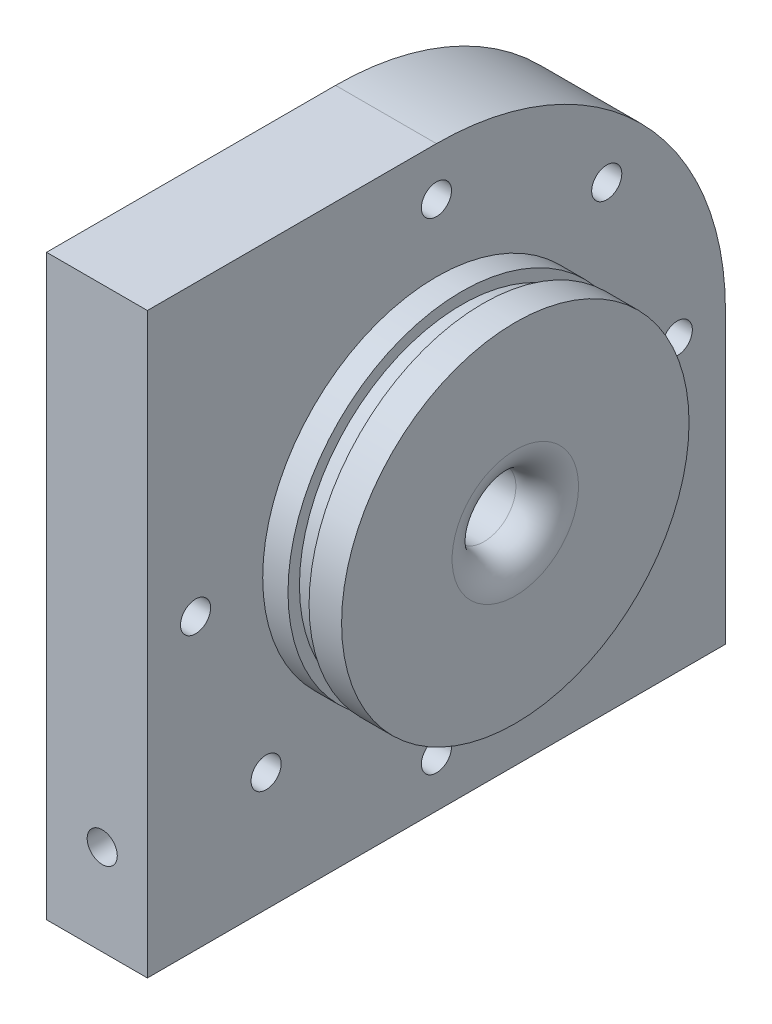
SolidWorks part; units mm, degrees
material "6061 Alloy"
ref_plane "Front Plane" through (0, 0, 0) normal (0, 0, 1) x (1, 0, 0)
ref_plane "Top Plane" through (0, 0, 0) normal (0, 1, 0) x (1, 0, 0)
ref_plane "Right Plane" through (0, 0, 0) normal (1, 0, 0) x (0, 0, -1)
sketch "Sketch1" plane through (0, 0, 0) normal (1, 0, 0) x (0, 0, -1)
  circle A0 centre (0, 0) radius 36.6395
  dimension "D1" = 73.279
extrude "Housing Fitting Extrude" add sketch "Sketch1" along normal blind 16.637
sketch "Sketch2" plane through (0, 0, 0) normal (-1, 0, 0) x (0, 0, 1)
  line L0 (60.96, 0) -> (60.96, 60.96)
  line L1 (60.96, 60.96) -> (0, 60.96)
  line L2 (60.96, 0) -> (60.96, -54.61)
  line L3 (60.96, -60.96) -> (-60.96, -60.96)
  line L7 (0, -55) -> (0, 55) construction
  line L11 (-60.96, 0) -> (-60.96, -54.61)
  line L12 (60.96, -60.96) -> (60.96, -54.61)
  line L13 (-60.96, -60.96) -> (-60.96, -54.61)
  arc A0 (0, 60.96) -> (-60.96, 0) centre (0, 0) ccw
extrude "Housing Body 1" add sketch "Sketch2" along normal blind 21.2725 contours A0 L11 L13 L3 L12 L2 L0 L1
sketch "Sketch3" plane through (16.637, 0, 0) normal (1, 0, 0) x (0, 0, -1)
  circle A0 centre (0, 0) radius 6.731
extrude "Impeller Bore" cut sketch "Sketch3" against normal blind 17.018
sketch "Sketch4" plane through (-0.381, 0, 0) normal (1, 0, 0) x (0, 0, -1)
  circle A0 centre (0, 0) radius 4
extrude "Shaft Bore" cut sketch "Sketch4" against normal up to surface (20.8915 mm away) up to face at (-21.2725, 2.525, -2.525)
ref_plane "O-Ring Sketch Plane" through (8.509, 0, 0) normal (1, 0, 0) x (0, 0, -1)
sketch "Sketch5" plane through (8.509, 0, 0) normal (1, 0, 0) x (0, 0, -1)
  circle A0 centre (0, 0) radius 36.6395
  circle A1 centre (0, 0) radius 34.2265
  dimension "D1" = 73.279
  dimension "D2" = 68.453
extrude "O-Ring Cut" cut sketch "Sketch5" against normal blind 3.175 and the other way blind 1.27
sketch "Sketch12" plane through (0, 0, 0) normal (1, 0, 0) x (0, 0, -1)
  line L0 (-60.96, 60.96) -> (0, 60.96) construction
  circle A0 centre (-50.8, 0) radius 3.175
  circle A1 centre (0, 0) radius 6.731 construction
  dimension "D1" = 50.8
  dimension "D3" = 6.35
  dimension "D2" = 60.96
extrude "Cut-Extrude2" cut sketch "Sketch12" against normal up to surface (21.2725 mm away) up to face at (-21.2725, 0, 4)
pattern_circular "CirPattern1" count 8 over 360 about axis through (0, 0, 0) along (1, 0, 0) skipping 7 of "Cut-Extrude2"
sketch "Sketch13" plane through (0, 0, 60.96) normal (0, 0, 1) x (1, 0, 0)
  circle A1 centre (-9.525, -41.8177) radius 3.175
extrude "Cut-Extrude3" cut sketch "Sketch13" against normal blind 16.51
sketch "Sketch14" plane through (0, -60.96, 0) normal (0, -1, 0) x (1, 0, 0)
  circle A0 centre (-9.525, -46.7543) radius 3.175
  circle A1 centre (-9.525, 41.9141) radius 3.3928
extrude "Cut-Extrude4" cut sketch "Sketch14" against normal blind 16.51
sketch "Sketch15" plane through (0, 0, -60.96) normal (0, 0, -1) x (-1, 0, 0)
  circle A0 centre (9.525, -39.3375) radius 3.175
extrude "Cut-Extrude5" cut sketch "Sketch15" against normal blind 10.922
fillet "Fillet1" radius 6.604 1 edges at (16.637, 0, -6.731)
sketch "Sketch17" plane through (-21.2725, 0, 0) normal (-1, 0, 0) x (0, 0, 1)
  circle A0 centre (0, 0) radius 17.5006
  dimension "D1" = 35.0012
extrude "Cut-Extrude8" cut sketch "Sketch17" against normal offset from surface (25.2095 mm away) 12.7 up to face at (16.637, 0, -13.335)
sketch "Sketch18" plane through (3.937, 0, 0) normal (-1, 0, 0) x (0, 0, 1)
  circle A0 centre (0, 0) radius 17.5006
  circle A1 centre (0, 0) radius 15.875
  circle A2 centre (0, 0) radius 17.5006 construction
  dimension "D1" = 35.0012
  dimension "D2" = 31.75
extrude "Boss-Extrude1" add sketch "Sketch18" along normal blind 6.35
equation "\"D1@Housing Body 1\"=1.563-0.67"
equation "\"D1\"= 0.2 + 0.3135 + 0.750"
